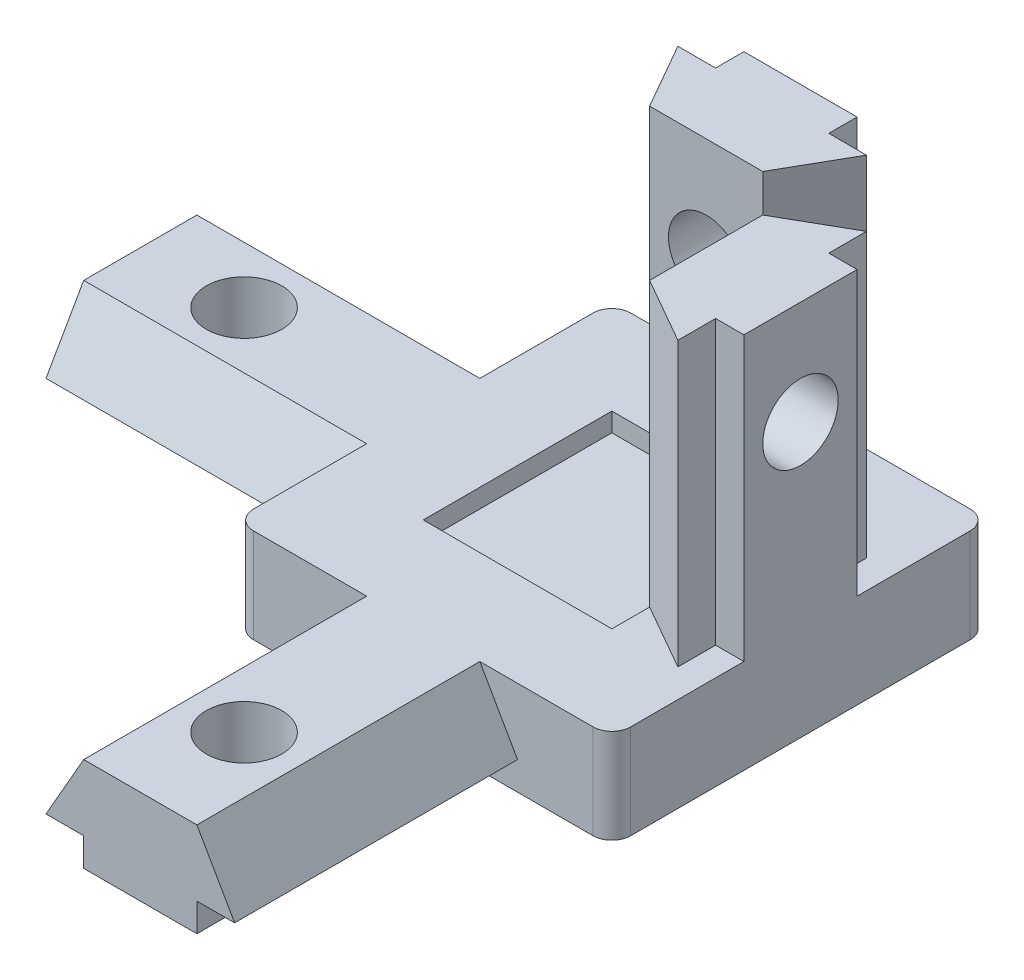
SolidWorks part; units mm, degrees
ref_plane "前视基准面" through (0, 0, 0) normal (0, 0, 1) x (1, 0, 0)
ref_plane "上视基准面" through (0, 0, 0) normal (0, 1, 0) x (1, 0, 0)
ref_plane "右视基准面" through (0, 0, 0) normal (1, 0, 0) x (0, 0, -1)
other "Configuration Table"
sketch "草图1" plane through (0, 0, 0) normal (0, 1, 0) x (1, 0, 0)
  line L1 (-10, 10) -> (10, 10)
  line L2 (-10, 10) -> (-10, -10)
  line L3 (-10, -10) -> (10, -10)
  line L4 (10, 10) -> (10, -10)
  line L5 (-10, 10) -> (10, -10) construction
  line L6 (-10, -10) -> (10, 10) construction
  point P0 (0, 0)
  dimension "D1" = 20
  dimension "D2" = 20
extrude "凸台-拉伸1" add sketch "草图1" along normal blind 5
sketch "草图2" plane through (0, 0, 10) normal (0, 0, 1) x (1, 0, 0)
  line L0 (0, 5) -> (0, 0) construction
  line L1 (-10, 5) -> (10, 5) construction
  line L2 (-3, 5) -> (3, 5)
  line L3 (3, 5) -> (5, 1.5)
  line L4 (5, 1.5) -> (3, 1.5)
  line L5 (3, 1.5) -> (3, 0)
  line L6 (-10, 0) -> (10, 0) construction
  line L7 (3, 0) -> (-3, 0)
  line L8 (-3, 1.5) -> (-3, 0)
  line L9 (-5, 1.5) -> (-3, 1.5)
  line L10 (-3, 5) -> (-5, 1.5)
  point P7 (2.3648, 5)
  dimension "D1" = 3.5
  dimension "D2" = 3
  dimension "D3" = 5
  dimension "D4" = 3
extrude "凸台-拉伸2" add sketch "草图2" along normal blind 15
sketch "草图3" plane through (-10, 0, 0) normal (-1, 0, 0) x (0, 0, 1)
  line L0 (0, 5) -> (0, 0) construction
  line L1 (-10, 5) -> (10, 5) construction
  line L2 (-3, 5) -> (3, 5)
  line L3 (3, 5) -> (5, 1.5)
  line L4 (5, 1.5) -> (3, 1.5)
  line L5 (3, 1.5) -> (3, 0)
  line L6 (-10, 0) -> (10, 0) construction
  line L7 (3, 0) -> (-3, 0)
  line L8 (-3, 1.5) -> (-3, 0)
  line L9 (-5, 1.5) -> (-3, 1.5)
  line L10 (-3, 5) -> (-5, 1.5)
  dimension "D1" = 3
  dimension "D2" = 3
  dimension "D3" = 5
  dimension "D4" = 3.5
extrude "凸台-拉伸3" add sketch "草图3" along normal blind 15
sketch "草图4" plane through (0, 5, 0) normal (0, 1, 0) x (1, 0, 0)
  line L0 (0, 10) -> (0, 0) construction
  line L1 (10, 10) -> (-10, 10) construction
  line L2 (0, 0) -> (10, 0) construction
  line L3 (10, -10) -> (10, 10) construction
  line L4 (-3, 10) -> (-3, 8.5)
  line L5 (-3, 8.5) -> (-5, 8.5)
  line L6 (-5, 8.5) -> (-3, 5)
  line L7 (-3, 5) -> (3, 5)
  line L8 (-3, 10) -> (3, 10)
  line L9 (5, 8.5) -> (3, 5)
  line L10 (3, 8.5) -> (5, 8.5)
  line L11 (3, 10) -> (3, 8.5)
  line L12 (0, 0) -> (10, 10) construction
  line L13 (8.5, -5) -> (5, -3)
  line L14 (8.5, -3) -> (8.5, -5)
  line L15 (10, -3) -> (8.5, -3)
  line L16 (10, -3) -> (10, 3)
  line L17 (10, 3) -> (8.5, 3)
  line L18 (8.5, 3) -> (8.5, 5)
  line L19 (8.5, 5) -> (5, 3)
  line L20 (5, -3) -> (5, 3)
  point P15 (0, 5)
  dimension "D1" = 3
  dimension "D2" = 3
  dimension "D3" = 3.5
  dimension "D4" = 5
  dimension "D5" = 1.5
extrude "凸台-拉伸4" add sketch "草图4" along normal blind 15
fillet "圆角1" radius 1 4 edges at (-10, 2.5, -10) (10, 2.5, -10) (10, 2.5, 10) (-10, 2.5, 10)
sketch "草图5" plane through (0, 5, 0) normal (0, 1, 0) x (1, 0, 0)
  line L0 (-3, 5) -> (3, 5) construction
  line L1 (-5, 5) -> (5, 5)
  line L2 (-5, 5) -> (-5, -5)
  line L3 (-5, -5) -> (5, -5)
  line L4 (5, 5) -> (5, -5)
  line L5 (-5, 5) -> (5, -5) construction
  line L6 (-5, -5) -> (5, 5) construction
  line L7 (5, 3) -> (5, -3) construction
  point P0 (0, 0)
extrude "切除-拉伸1" cut sketch "草图5" against normal blind 1
sketch "草图6" plane through (0, 5, 0) normal (0, 1, 0) x (1, 0, 0)
  line L0 (0, -25) -> (0, 0) construction
  line L1 (3, -25) -> (-3, -25) construction
  line L2 (0, 0) -> (-25, 0) construction
  line L3 (-25, -3) -> (-25, 3) construction
  circle A0 centre (0, -19.5) radius 2
  circle A1 centre (-19.5, 0) radius 2
  dimension "D1" = 4
  dimension "D3" = 4
  dimension "D2" = 5.5
  dimension "D4" = 5.5
extrude "切除-拉伸2" cut sketch "草图6" against normal up to next
sketch "草图7" plane through (5, 0, 0) normal (-1, 0, 0) x (0, 0, 1)
  line L0 (0, 20) -> (0, 5) construction
  line L1 (-3, 20) -> (3, 20) construction
  line L2 (3, 5) -> (-3, 5) construction
  circle A0 centre (0, 14.5) radius 2
  dimension "D1" = 4
  dimension "D2" = 5.5
extrude "切除-拉伸3" cut sketch "草图7" against normal up to next
sketch "草图8" plane through (0, 0, -5) normal (0, 0, 1) x (1, 0, 0)
  line L0 (0, 20) -> (0, 5) construction
  line L1 (-3, 20) -> (3, 20) construction
  line L2 (3, 5) -> (-3, 5) construction
  circle A0 centre (0, 14.5) radius 2
  dimension "D1" = 4
  dimension "D2" = 5.5
extrude "切除-拉伸4" cut sketch "草图8" against normal up to next
